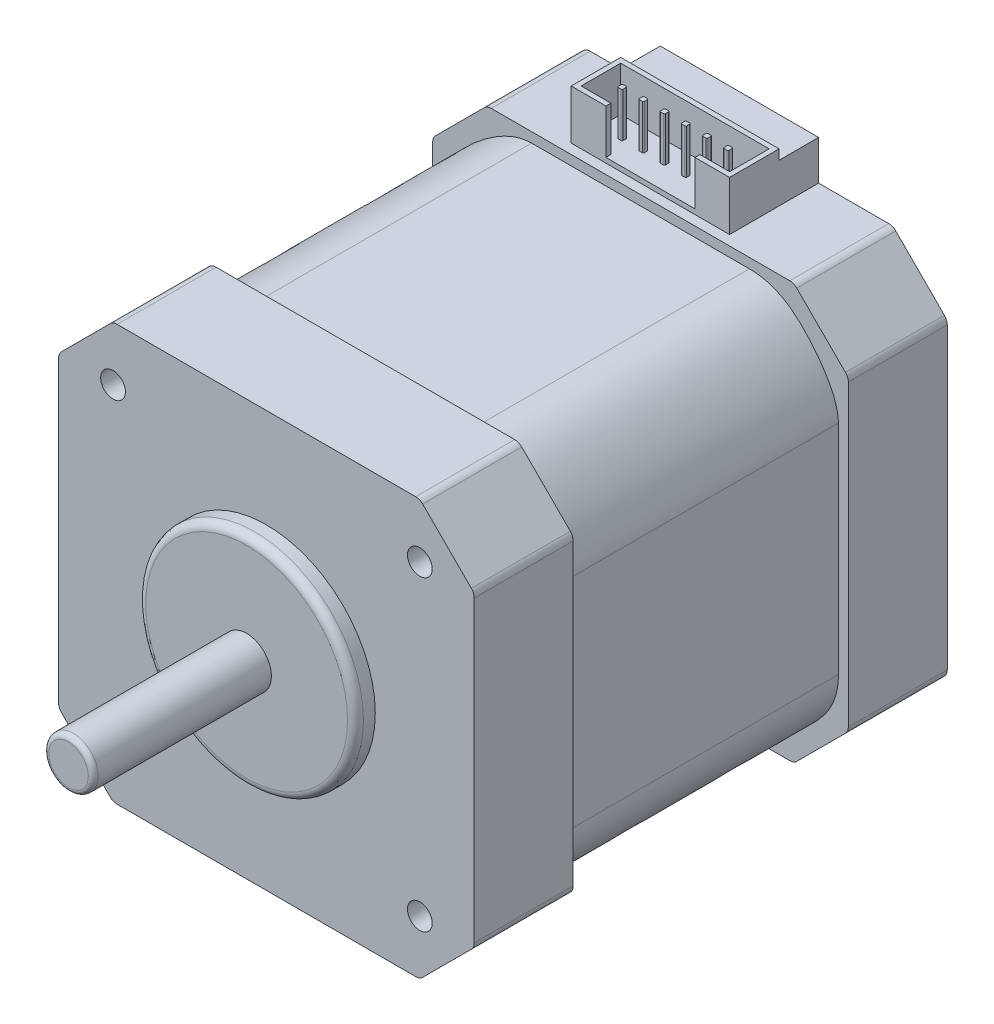
SolidWorks part; units mm, degrees
ref_plane "前视" through (0, 0, 0) normal (0, 0, 1) x (1, 0, 0)
ref_plane "上视" through (0, 0, 0) normal (0, 1, 0) x (1, 0, 0)
ref_plane "右视" through (0, 0, 0) normal (1, 0, 0) x (0, 0, -1)
sketch "草图1" plane through (0, 0, 0) normal (0, 0, 1) x (1, 0, 0)
  line L0 (15.5, 21) -> (21, 15.5)
  line L1 (-15.5, 21) -> (15.5, 21)
  line L2 (-21, 15.5) -> (-21, -15.5)
  line L3 (-15.5, -21) -> (15.5, -21)
  line L4 (21, 15.5) -> (21, -15.5)
  line L5 (-18.25, 18.25) -> (18.25, -18.25) construction
  line L6 (-18.25, -18.25) -> (18.25, 18.25) construction
  line L7 (21, -15.5) -> (15.5, -21)
  line L8 (-15.5, -21) -> (-21, -15.5)
  line L9 (-21, 15.5) -> (-15.5, 21)
  point P0 (0, 0)
  point P17 (2.5, 2.5)
  point P18 (0, 0)
  dimension "D1" = 42
  dimension "D2" = 315
  dimension "D3" = 90
  dimension "D4" = 15.5
  dimension "D6" = 21
  dimension "D7" = 21
  dimension "D5" = 4
extrude "凸台-拉伸1" add sketch "草图1" along normal blind 10
sketch "草图2" plane through (0, 0, 10) normal (0, 0, 1) x (1, 0, 0)
  line L0 (-20, 12.0072) -> (-20, 7.7817) construction
  line L1 (-11, 20) -> (11, 20)
  line L2 (-20, 11) -> (-20, -11)
  line L3 (-11, -20) -> (11, -20)
  line L4 (20, 11) -> (20, -11)
  line L5 (-20, 20) -> (20, -20) construction
  line L6 (-20, -20) -> (20, 20) construction
  line L7 (-8.6523, 20) -> (-11.7517, 20) construction
  spline S0 degree 3 poles (-20, 11) (-20, 13.6409) (-17.4726, 17.1207) (-12.9371, 20) (-11, 20) knots 0 0 0 0 0.5 1 1 1 1
  spline S1 degree 3 poles (11, 20) (13.6409, 20) (17.1207, 17.4726) (20, 12.9371) (20, 11) knots 0 0 0 0 0.5 1 1 1 1
  spline S2 degree 3 poles (20, -11) (20, -13.6409) (17.4726, -17.1207) (12.9371, -20) (11, -20) knots 0 0 0 0 0.5 1 1 1 1
  spline S3 degree 3 poles (-11, -20) (-13.6409, -20) (-17.1207, -17.4726) (-20, -12.9371) (-20, -11) knots 0 0 0 0 0.5 1 1 1 1
  point P0 (0, 0)
  point P25 (0, 0)
  dimension "D1" = 40
  dimension "D2" = 40
  dimension "D3" = 11
  dimension "D4" = 11
  dimension "D5" = 24
extrude "凸台-拉伸2" add sketch "草图2" along normal blind 27.8
sketch "草图3" plane through (0, 0, 37.8) normal (0, 0, 1) x (1, 0, 0)
  line L8 (21, -15.5) -> (21, 15.5)
  line L9 (15.5, -21) -> (21, -15.5)
  line L10 (-15.5, -21) -> (15.5, -21)
  line L11 (-21, -15.5) -> (-15.5, -21)
  line L12 (-21, 15.5) -> (-21, -15.5)
  line L13 (-15.5, 21) -> (-21, 15.5)
  line L14 (15.5, 21) -> (-15.5, 21)
  line L15 (21, 15.5) -> (15.5, 21)
  line L16 (21, -15.5) -> (21, 15.5)
  line L17 (15.5, -21) -> (21, -15.5)
  line L18 (-15.5, -21) -> (15.5, -21)
  line L19 (-21, -15.5) -> (-15.5, -21)
  line L20 (-21, 15.5) -> (-21, -15.5)
  line L21 (-15.5, 21) -> (-21, 15.5)
  line L22 (15.5, 21) -> (-15.5, 21)
  line L23 (21, 15.5) -> (15.5, 21)
  dimension "D1" = 0
extrude "凸台-拉伸3" add sketch "草图3" along normal blind 10
sketch "草图4" plane through (0, 0, 47.8) normal (0, 0, 1) x (1, 0, 0)
  circle A0 centre (0, 0) radius 11
extrude "凸台-拉伸4" add sketch "草图4" along normal blind 2
sketch "草图5" plane through (0, 0, 49.8) normal (0, 0, 1) x (1, 0, 0)
  circle A0 centre (0, 0) radius 2.5
  dimension "D1" = 5
extrude "凸台-拉伸5" add sketch "草图5" along normal blind 18 contours A0
fillet "圆角1" radius 0.5 1 edges at (2.5, 0, 67.8)
fillet "圆角2" radius 0.8 1 edges at (11, 0, 49.8)
fillet "圆角3" radius 1 8 edges at (15.5, 21, 5) (21, 15.5, 5) (21, -15.5, 5) (15.5, -21, 5) (-15.5, -21, 5) (-21, -15.5, 5) (-15.5, 21, 5) (-21, 15.5, 5)
fillet "圆角4" radius 1 8 edges at (-21, -15.5, 42.8) (-15.5, -21, 42.8) (15.5, -21, 42.8) (21, -15.5, 42.8) (21, 15.5, 42.8) (15.5, 21, 42.8) (-15.5, 21, 42.8) (-21, 15.5, 42.8)
sketch "草图13" plane through (0, 0, 47.8) normal (0, 0, 1) x (1, 0, 0)
  line L0 (0, 0) -> (0, 27.4188) construction
  line L1 (0, 0) -> (30.8326, 0) construction
  circle A0 centre (-15.5, 15.5) radius 1.5
  circle A1 centre (15.5, 15.5) radius 1.5
  circle A2 centre (15.5, -15.5) radius 1.5
  circle A3 centre (-15.5, -15.5) radius 1.5
  dimension "D3" = 3
  dimension "D4" = 3
  dimension "D5" = 3
  dimension "D6" = 3
  dimension "D1" = 31
  dimension "D2" = 31
hole_wizard "M3 螺纹孔4" positions "3D草图7" profile "草图17" tap size "M3" standard "GB"
sketch3d "3D草图7"
  point P0 (-15.5, 15.5, 47.8)
  point P3 (15.5, 15.5, 47.8)
  point P6 (15.5, -15.5, 47.8)
  point P9 (-15.5, -15.5, 47.8)
sketch "草图17" plane through (-15.5, 15.5, 47.8) normal (1, 0, 0) x (0, -1, 0)
  line L0 (0, 0) -> (0, 9.7511)
  line L1 (0, 9.7511) -> (1.25, 9)
  line L2 (1.25, 9) -> (1.25, 0)
  line L5 (1.25, 0) -> (0, 0)
  line L10 (0, 9.7511) -> (-1.25, 9) construction
  line L11 (0, -6.35) -> (0, 107.95) construction
  dimension "螺纹孔钻头直径" = 2.5
  dimension "螺纹孔钻头深度" = 9
  dimension "导头角度" = 118
cosmetic thread "孔螺蚊线13" parameters "D1"=9, "D2"=3
cosmetic thread "孔螺蚊线14" parameters "D1"=9, "D2"=3
cosmetic thread "孔螺蚊线15" parameters "D1"=9, "D2"=3
cosmetic thread "孔螺蚊线16" parameters "D1"=9, "D2"=3
sketch "草图18" plane through (0, 0, 0) normal (0, 0, -1) x (-1, 0, 0)
  line L0 (-8, 25) -> (-8, 21)
  line L1 (-8, 25) -> (8, 25)
  line L2 (-8, 21) -> (8, 21)
  line L3 (8, 25) -> (8, 21)
  line L4 (-8, 25) -> (8, 21) construction
  line L5 (-8, 21) -> (8, 25) construction
  line L6 (0, 0) -> (0, 27.4188) construction
  line L7 (0, 0) -> (0, 11.7867) construction
  line L10 (-15.0858, 21) -> (15.0858, 21) construction
  line L11 (-15.0858, 21) -> (15.0858, 21)
  point P1 (0, 23)
  dimension "D1" = 16
  dimension "D2" = 4
extrude "凸台-拉伸6" add sketch "草图18" against normal blind 4 contours L1 L3 L2 L0
sketch "草图19" plane through (0, 0, 4) normal (0, 0, 1) x (1, 0, 0)
  line L0 (-8, 26) -> (-8, 21)
  line L1 (-8, 26) -> (8, 26)
  line L2 (-8, 21) -> (8, 21)
  line L3 (8, 26) -> (8, 21)
  line L4 (-8, 26) -> (8, 21) construction
  line L5 (-8, 21) -> (8, 26) construction
  line L7 (0, 0) -> (0, 27.4188) construction
  point P1 (0, 23.5)
  dimension "D1" = 16
  dimension "D2" = 5
extrude "凸台-拉伸7" add sketch "草图19" along normal blind 5
sketch "草图20" plane through (0, 26, 0) normal (0, 1, 0) x (1, 0, 0)
  line L0 (-7.5, -4.5) -> (7.5, -4.5)
  line L1 (-7.5, -4.5) -> (-7.5, -8.5)
  line L2 (7.5, -4.5) -> (7.5, -8.5)
  line L3 (-7.5, -8.5) -> (7.5, -8.5)
  line L4 (-7.5, -4.5) -> (7.5, -8.5) construction
  line L5 (7.5, -4.5) -> (-7.5, -8.5) construction
  line L7 (8, -4) -> (-8, -4) construction
  line L8 (-8, -9) -> (-8, 0) construction
  point P1 (0, -6.5)
  dimension "D1" = 15
  dimension "D2" = 4
  dimension "D3" = 0.5
  dimension "D4" = 0.5
extrude "切除-拉伸2" cut sketch "草图20" against normal offset from surface (4.5 mm away) 0.5 up to face at (0, 21, 4.75)
sketch "草图22" plane through (0, 0, 9) normal (0, 0, 1) x (1, 0, 0)
  line L0 (0, 21) -> (0, 26) construction
  line L1 (-8, 21) -> (8, 21) construction
  line L2 (8, 26) -> (-8, 26) construction
  line L4 (-4.5, 21.5) -> (4.5, 21.5)
  line L5 (-4.5, 21.5) -> (-4.5, 26)
  line L6 (-4.5, 26) -> (4.5, 26)
  line L7 (4.5, 21.5) -> (4.5, 26)
  line L8 (-4.5, 21.5) -> (4.5, 26) construction
  line L9 (-4.5, 26) -> (4.5, 21.5) construction
  point P6 (0, 23.75)
  dimension "D1" = 9
  dimension "D2" = 4.5
extrude "切除-拉伸3" cut sketch "草图22" against normal blind 0.5
sketch "草图23" plane through (0, 21.5, 0) normal (0, 1, 0) x (1, 0, 0)
  line L0 (-3.46, -6.25) -> (-2.96, -6.25)
  line L1 (-5.6, -6.25) -> (-5.1, -6.25)
  line L2 (-5.6, -6.25) -> (-5.6, -6.75)
  line L3 (-5.6, -6.75) -> (-5.1, -6.75)
  line L4 (-5.1, -6.25) -> (-5.1, -6.75)
  line L5 (-5.6, -6.25) -> (-5.1, -6.75) construction
  line L6 (-5.6, -6.75) -> (-5.1, -6.25) construction
  line L7 (-2.96, -6.25) -> (-2.96, -6.75)
  line L8 (-3.46, -6.75) -> (-2.96, -6.75)
  line L9 (-3.46, -6.25) -> (-3.46, -6.75)
  line L10 (-1.32, -6.25) -> (-0.82, -6.25)
  line L11 (-0.82, -6.25) -> (-0.82, -6.75)
  line L12 (-1.32, -6.75) -> (-0.82, -6.75)
  line L13 (-1.32, -6.25) -> (-1.32, -6.75)
  line L14 (0.82, -6.25) -> (1.32, -6.25)
  line L15 (1.32, -6.25) -> (1.32, -6.75)
  line L16 (0.82, -6.75) -> (1.32, -6.75)
  line L17 (0.82, -6.25) -> (0.82, -6.75)
  line L18 (2.96, -6.25) -> (3.46, -6.25)
  line L19 (3.46, -6.25) -> (3.46, -6.75)
  line L20 (2.96, -6.75) -> (3.46, -6.75)
  line L21 (2.96, -6.25) -> (2.96, -6.75)
  line L22 (5.1, -6.25) -> (5.6, -6.25)
  line L23 (5.6, -6.25) -> (5.6, -6.75)
  line L24 (5.1, -6.75) -> (5.6, -6.75)
  line L25 (5.1, -6.25) -> (5.1, -6.75)
  line L26 (-7.5, -6.5) -> (-5.8752, -6.5) construction
  line L27 (-7.5, -4.5) -> (-7.5, -8.5) construction
  line L31 (-7.5, -4.5) -> (-7.5, -8.5) construction
  point P0 (-5.35, -6.5)
  dimension "D1" = 0.5
  dimension "D2" = 0.5
  dimension "D4" = 1.9
  dimension "D3" = 6
extrude "凸台-拉伸8" add sketch "草图23" along normal up to surface (4.5 mm away) up to face at (0, 26, 7.25)
fillet "圆角6" radius 0.1 4 edges at (-5.1, 23.75, 6.25) (-5.6, 23.75, 6.25) (-5.6, 23.75, 6.75) (-5.1, 23.75, 6.75)
fillet "圆角7" radius 0.1 4 edges at (-2.96, 23.75, 6.25) (-3.46, 23.75, 6.25) (-3.46, 23.75, 6.75) (-2.96, 23.75, 6.75)
fillet "圆角8" radius 0.1 4 edges at (-0.82, 23.75, 6.25) (-1.32, 23.75, 6.25) (-1.32, 23.75, 6.75) (-0.82, 23.75, 6.75)
fillet "圆角9" radius 0.1 4 edges at (0.82, 23.75, 6.25) (1.32, 23.75, 6.25) (0.82, 23.75, 6.75) (1.32, 23.75, 6.75)
fillet "圆角10" radius 0.1 4 edges at (2.96, 23.75, 6.25) (3.46, 23.75, 6.25) (3.46, 23.75, 6.75) (2.96, 23.75, 6.75)
fillet "圆角11" radius 0.1 4 edges at (5.6, 23.75, 6.75) (5.6, 23.75, 6.25) (5.1, 23.75, 6.25) (5.1, 23.75, 6.75)
sketch "草图24" plane through (0, 0, 47.8) normal (0, 0, 1) x (1, 0, 0)
  line L8 (21, -15.5) -> (21, 15.5)
  line L9 (21, 15.5) -> (15.5, 21)
  line L10 (15.5, 21) -> (-15.5, 21)
  line L11 (-15.5, 21) -> (-21, 15.5)
  line L12 (-21, 15.5) -> (-21, -15.5)
  line L13 (-21, -15.5) -> (-15.5, -21)
  line L14 (-15.5, -21) -> (15.5, -21)
  line L15 (15.5, -21) -> (21, -15.5)
  line L16 (21, -15.5) -> (21, 15.5)
  line L17 (21, 15.5) -> (15.5, 21)
  line L18 (15.5, 21) -> (-15.5, 21)
  line L19 (-15.5, 21) -> (-21, 15.5)
  line L20 (-21, 15.5) -> (-21, -15.5)
  line L21 (-21, -15.5) -> (-15.5, -21)
  line L22 (-15.5, -21) -> (15.5, -21)
  line L23 (15.5, -21) -> (21, -15.5)
  circle A0 centre (0, 0) radius 11 construction
  circle A1 centre (-15.5, -15.5) radius 1.5
  circle A2 centre (-15.5, -15.5) radius 1.5 construction
  circle A3 centre (15.5, -15.5) radius 1.5
  circle A4 centre (15.5, -15.5) radius 1.5 construction
  circle A5 centre (15.5, 15.5) radius 1.5
  circle A6 centre (15.5, 15.5) radius 1.5 construction
  circle A7 centre (-15.5, 15.5) radius 1.5
  circle A8 centre (-15.5, 15.5) radius 1.5 construction
  circle A9 centre (0, 0) radius 11
  circle A10 centre (0, 0) radius 11.2
  circle A11 centre (-15.5, 15.5) radius 1.7
  circle A12 centre (15.5, 15.5) radius 1.7
  circle A13 centre (15.5, -15.5) radius 1.7
  circle A14 centre (-15.5, -15.5) radius 1.7
  dimension "D1" = 0
  dimension "D2" = 0
  dimension "D3" = 0
  dimension "D4" = 0
  dimension "D5" = 0
  dimension "D6" = 0.2
